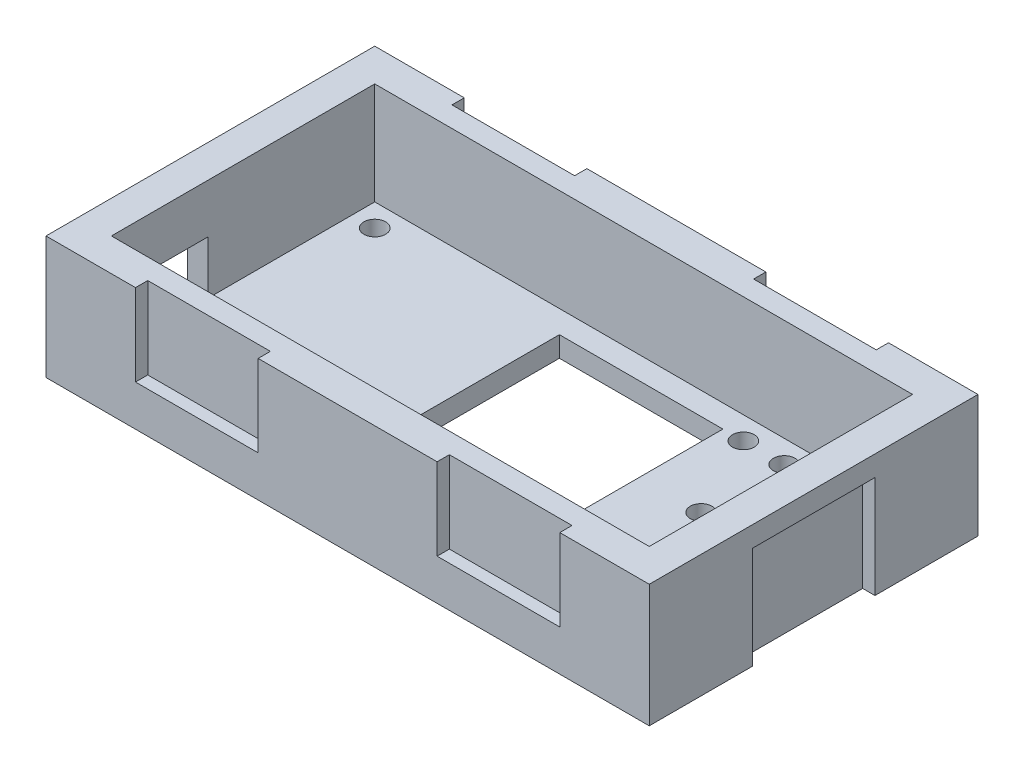
SolidWorks part; units mm, degrees
ref_plane "Front Plane" through (0, 0, 0) normal (0, 0, 1) x (1, 0, 0)
ref_plane "Top Plane" through (0, 0, 0) normal (0, 1, 0) x (1, 0, 0)
ref_plane "Right Plane" through (0, 0, 0) normal (1, 0, 0) x (0, 0, -1)
sketch "Sketch1" plane through (0, 0, 0) normal (0, 1, 0) x (1, 0, 0)
  line L1 (0, 0) -> (147.57, 0)
  line L2 (0, 0) -> (0, 80.42)
  line L3 (0, 80.42) -> (147.57, 80.42)
  line L4 (147.57, 0) -> (147.57, 80.42)
  line L5 (0, 0) -> (147.57, 80.42) construction
  line L6 (0, 80.42) -> (147.57, 0) construction
  point P4 (73.785, 40.21)
  dimension "D1" = 80.42
  dimension "D2" = 147.57
extrude "Boss-Extrude1" add sketch "Sketch1" along normal blind 30
sketch "Sketch2" plane through (0, 30, 0) normal (0, 1, 0) x (1, 0, 0)
  line L0 (147.57, 80.42) -> (0, 80.42) construction
  line L1 (8, 72.42) -> (139.57, 72.42)
  line L2 (8, 72.42) -> (8, 8)
  line L3 (8, 8) -> (139.57, 8)
  line L4 (139.57, 72.42) -> (139.57, 8)
  line L5 (8, 72.42) -> (139.57, 8) construction
  line L6 (8, 8) -> (139.57, 72.42) construction
  line L7 (0, 80.42) -> (0, 0) construction
  line L8 (0, 0) -> (147.57, 0) construction
  line L9 (147.57, 0) -> (147.57, 80.42) construction
  point P4 (73.785, 40.21)
  dimension "D1" = 8
  dimension "D2" = 8
  dimension "D3" = 8
  dimension "D4" = 8
extrude "Cut-Extrude1" cut sketch "Sketch2" against normal blind 25
sketch "Sketch3" plane through (0, 5, 0) normal (0, 1, 0) x (1, 0, 0)
  line L0 (8, 8) -> (139.57, 8) construction
  line L1 (13.54, 13.54) -> (103.71, 13.54) construction
  line L2 (13.54, 13.54) -> (13.54, 66.88) construction
  line L3 (13.54, 66.88) -> (103.71, 66.88) construction
  line L4 (103.71, 13.54) -> (103.71, 66.88) construction
  line L5 (13.54, 13.54) -> (103.71, 66.88) construction
  line L6 (13.54, 66.88) -> (103.71, 13.54) construction
  line L7 (8, 72.42) -> (8, 8) construction
  line L9 (113.71, 66.88) -> (134.03, 66.88) construction
  line L10 (113.71, 66.88) -> (113.71, 46.56) construction
  line L11 (113.71, 46.56) -> (134.03, 46.56) construction
  line L12 (134.03, 66.88) -> (134.03, 46.56) construction
  line L13 (113.71, 66.88) -> (134.03, 46.56) construction
  line L14 (113.71, 46.56) -> (134.03, 66.88) construction
  line L15 (113.71, 13.54) -> (128.95, 13.54) construction
  line L16 (113.71, 13.54) -> (113.71, 28.78) construction
  line L17 (113.71, 28.78) -> (128.95, 28.78) construction
  line L18 (128.95, 13.54) -> (128.95, 28.78) construction
  line L19 (113.71, 13.54) -> (128.95, 28.78) construction
  line L20 (113.71, 28.78) -> (128.95, 13.54) construction
  point P4 (58.625, 40.21)
  point P13 (123.87, 56.72)
  point P18 (121.33, 21.16)
  dimension "D1" = 5.54
  dimension "D2" = 5.54
  dimension "D3" = 90.17
  dimension "D4" = 53.34
  dimension "D5" = 20.32
  dimension "D6" = 20.32
  dimension "D7" = 15.24
  dimension "D8" = 15.24
  dimension "D9" = 10
  dimension "D10" = 0
  dimension "D11" = 0
hole_wizard "#4 (0.209) Diameter Hole1" positions "3DSketch2" profile "Sketch6" hole size "#4" standard "ANSI Inch" end condition through all
sketch3d "3DSketch2"
  point P0 (13.54, 5, -66.88)
  point P3 (13.54, 5, -13.54)
  point P6 (103.71, 5, -13.54)
  point P9 (113.71, 5, -13.54)
  point P12 (113.71, 5, -28.78)
  point P15 (128.95, 5, -28.78)
  point P18 (128.95, 5, -13.54)
  point P21 (134.03, 5, -46.56)
  point P24 (134.03, 5, -66.88)
  point P27 (113.71, 5, -66.88)
  point P30 (113.71, 5, -46.56)
  point P33 (103.71, 5, -66.88)
sketch "Sketch6" plane through (13.54, 5, -66.88) normal (1, 0, 0) x (0, 0, 1)
  line L0 (0, 0) -> (0, 5)
  line L1 (0, 5) -> (2.6543, 5)
  line L2 (2.6543, 5) -> (2.6543, 0)
  line L5 (2.6543, 0) -> (0, 0)
  line L11 (0, -6.35) -> (0, 107.95) construction
  dimension "Thru Hole Dia." = 5.3086
  dimension "Thru Hole Depth" = 5
sketch3d "3DSketch3"
  line L0 (73.785, 0, 0) -> (73.785, 30, 0) construction
  line L1 (0, 0, 0) -> (147.57, 0, 0) construction
  line L2 (0, 30, 0) -> (147.57, 30, 0) construction
  line L3 (147.57, 0, -40.21) -> (147.57, 30, -40.21) construction
  line L4 (147.57, 0, 0) -> (147.57, 0, -80.42) construction
  line L5 (147.57, 30, 0) -> (147.57, 30, -80.42) construction
  line L6 (73.785, 0, -80.42) -> (73.785, 30, -80.42) construction
  line L7 (147.57, 0, -80.42) -> (0, 0, -80.42) construction
  line L8 (147.57, 30, -80.42) -> (0, 30, -80.42) construction
  line L9 (0, 0, -40.21) -> (0, 30, -40.21) construction
  line L10 (0, 0, -80.42) -> (0, 0, 0) construction
  dimension "D1" = 30
ref_plane "Plane1" through (0, 0, -40.21) normal (0, 0, -1) x (-1, 0, 0)
ref_plane "Plane2" through (73.785, 0, 0) normal (1, 0, 0) x (0, 0, -1)
sketch "Sketch13" plane through (0, 0, -80.42) normal (0, 0, -1) x (-1, 0, 0)
  line L0 (-147.57, 30) -> (0, 30) construction
  line L1 (-125.6775, 30) -> (-95.6775, 30)
  line L2 (-125.6775, 30) -> (-125.6775, 10)
  line L3 (-125.6775, 10) -> (-95.6775, 10)
  line L4 (-95.6775, 30) -> (-95.6775, 10)
  line L5 (-125.6775, 30) -> (-95.6775, 10) construction
  line L6 (-125.6775, 10) -> (-95.6775, 30) construction
  line L7 (-147.57, 30) -> (-147.57, 0) construction
  point P4 (-110.6775, 20)
  dimension "D1" = 20
  dimension "D2" = 30
  dimension "D3" = 36.8925
extrude "Cut-Extrude3" cut sketch "Sketch13" against normal blind 3
sketch "Sketch14" plane through (8, 0, 0) normal (1, 0, 0) x (0, 0, -1)
  line L0 (0, 30) -> (0, 0) construction
  line L1 (72.42, 30) -> (8, 30) construction
  point P0 (40.21, 20)
  dimension "D1" = 40.21
  dimension "D2" = 10
mirror "Mirror2" about plane through (73.785, 0, 0) normal (1, 0, 0) of "Cut-Extrude3"
mirror "Mirror3" about plane through (0, 0, -40.21) normal (0, 0, -1) of "Mirror2", "Cut-Extrude3"
sketch "Sketch17" plane through (0, 0, -72.42) normal (0, 0, 1) x (1, 0, 0)
  line L0 (139.57, 30) -> (8, 30) construction
  line L1 (0, 30) -> (0, 0) construction
  point P0 (36.8925, 20)
  dimension "D1" = 10
  dimension "D2" = 36.8925
hole_wizard "CBORE for #4 Binding Head Machine Screw2" [suppressed] positions "3DSketch5" profile "Sketch18" counterbore size "#4" standard "ANSI Inch"
sketch3d "3DSketch5"
  point P0 (36.8925, 20, -72.42)
sketch "Sketch18" plane through (36.8925, 20, -72.42) normal (1, 0, 0) x (0, -1, 0)
  line L0 (0, 0) -> (0, 8)
  line L1 (0, 8) -> (1.7272, 8)
  line L3 (1.7272, 8) -> (1.7272, 1.7272)
  line L4 (1.7272, 1.7272) -> (3.3731, 1.7272)
  line L5 (3.3731, 1.7272) -> (3.3731, 0)
  line L7 (3.3731, 0) -> (0, 0)
  line L11 (0, -6.35) -> (0, 107.95) construction
  dimension "Thru Hole Dia." = 3.4544
  dimension "Thru Hole Depth" = 8
  dimension "C'Bore Dia." = 6.7462
  dimension "C'Bore Depth" = 1.7272
mirror "Mirror5" [suppressed] about plane through (73.785, 0, 0) normal (1, 0, 0)
mirror "Mirror6" [suppressed] about plane through (0, 0, -40.21) normal (0, 0, -1)
sketch "Sketch19" plane through (0, 0, 0) normal (-1, 0, 0) x (0, 0, 1)
  line L0 (-80.42, 0) -> (0, 0) construction
  line L1 (-55.21, 0) -> (-25.21, 0)
  line L2 (-55.21, 0) -> (-55.21, 25)
  line L3 (-55.21, 25) -> (-25.21, 25)
  line L4 (-25.21, 0) -> (-25.21, 25)
  line L5 (-55.21, 0) -> (-25.21, 25) construction
  line L6 (-55.21, 25) -> (-25.21, 0) construction
  line L7 (0, 30) -> (0, 0) construction
  point P4 (-40.21, 12.5)
  dimension "D1" = 25
  dimension "D2" = 30
  dimension "D3" = 40.21
extrude "Cut-Extrude4" cut sketch "Sketch19" against normal blind 3
sketch "Sketch20" plane through (3, 0, 0) normal (-1, 0, 0) x (0, 0, 1)
  line L0 (-40.21, 16.5) -> (-40.21, -16.5) construction
  point P0 (-40.21, 13)
  dimension "D1" = 7
sketch "Sketch23" plane through (8, 0, 0) normal (1, 0, 0) x (0, 0, -1)
  line L0 (40.21, 30) -> (40.21, 20) construction
  line L1 (72.42, 30) -> (8, 30) construction
  dimension "D1" = 10
hole_wizard "CBORE for #4 Binding Head Machine Screw3" [suppressed] positions "3DSketch6" profile "Sketch24" counterbore size "#4" standard "ANSI Inch"
sketch3d "3DSketch6"
  point P0 (8, 20, -40.21)
sketch "Sketch24" plane through (8, 20, -40.21) normal (0, 1, 0) x (0, 0, -1)
  line L0 (0, 0) -> (0, 8)
  line L1 (0, 8) -> (1.7272, 8)
  line L3 (1.7272, 8) -> (1.7272, 1.7272)
  line L4 (1.7272, 1.7272) -> (3.3731, 1.7272)
  line L5 (3.3731, 1.7272) -> (3.3731, 0)
  line L7 (3.3731, 0) -> (0, 0)
  line L11 (0, -6.35) -> (0, 107.95) construction
  dimension "Thru Hole Dia." = 3.4544
  dimension "Thru Hole Depth" = 8
  dimension "C'Bore Dia." = 6.7462
  dimension "C'Bore Depth" = 1.7272
mirror "Mirror7" about plane through (73.785, 0, 0) normal (1, 0, 0) of "Cut-Extrude4"
mirror "Mirror8" [suppressed] about plane through (73.785, 0, 0) normal (1, 0, 0)
sketch "Sketch25" plane through (0, 5, 0) normal (0, 1, 0) x (1, 0, 0)
  line L0 (13.54, 66.88) -> (103.71, 66.88) construction
  line L1 (58.71, 66.88) -> (98.71, 66.88)
  line L2 (58.71, 66.88) -> (58.71, 13.54)
  line L3 (58.71, 13.54) -> (98.71, 13.54)
  line L4 (98.71, 66.88) -> (98.71, 13.54)
  line L5 (58.71, 66.88) -> (98.71, 13.54) construction
  line L6 (58.71, 13.54) -> (98.71, 66.88) construction
  line L7 (13.54, 13.54) -> (103.71, 13.54) construction
  line L8 (103.71, 13.54) -> (103.71, 66.88) construction
  circle A0 centre (13.54, 66.88) radius 2.6543 construction
  point P4 (78.71, 40.21)
  point P9 (16.1943, 66.88)
  dimension "D1" = 5
  dimension "D2" = 40
extrude "Cut-Extrude5" cut sketch "Sketch25" against normal through all
sketch3d "3DSketch7"
  line L0 (13.54, 5, -13.54) -> (13.54, 5, -66.88) construction
  line L1 (13.54, 5, -16.1943) -> (8, 5, -16.1943) construction
  line L2 (8, 5, -72.42) -> (8, 5, -8) construction
  circle A0 centre (13.54, 5, -13.54) radius 2.6543 construction
  point P0 (13.54, 5, -16.1943)
  point P6 (13.54, 7.6543, -13.54)
sketch "Sketch30" plane through (8, 0, 0) normal (1, 0, 0) x (0, 0, -1)
  line L0 (0, 30) -> (0, 0) construction
  line L1 (11.605, 18) -> (31.605, 18)
  line L2 (11.605, 18) -> (11.605, 6)
  line L3 (11.605, 6) -> (31.605, 6)
  line L4 (31.605, 18) -> (31.605, 6)
  line L5 (11.605, 18) -> (31.605, 6) construction
  line L6 (11.605, 6) -> (31.605, 18) construction
  line L8 (25.21, 0) -> (25.21, 25) construction
  line L9 (25.21, 21.9849) -> (8, 21.9849) construction
  line L11 (72.42, 5) -> (8, 5) construction
  point P4 (21.605, 12)
  dimension "D1" = 20
  dimension "D2" = 11.605
  dimension "D3" = 8
  dimension "D4" = 12
  dimension "D5" = 1
extrude "Cut-Extrude7" cut sketch "Sketch30" against normal through all
